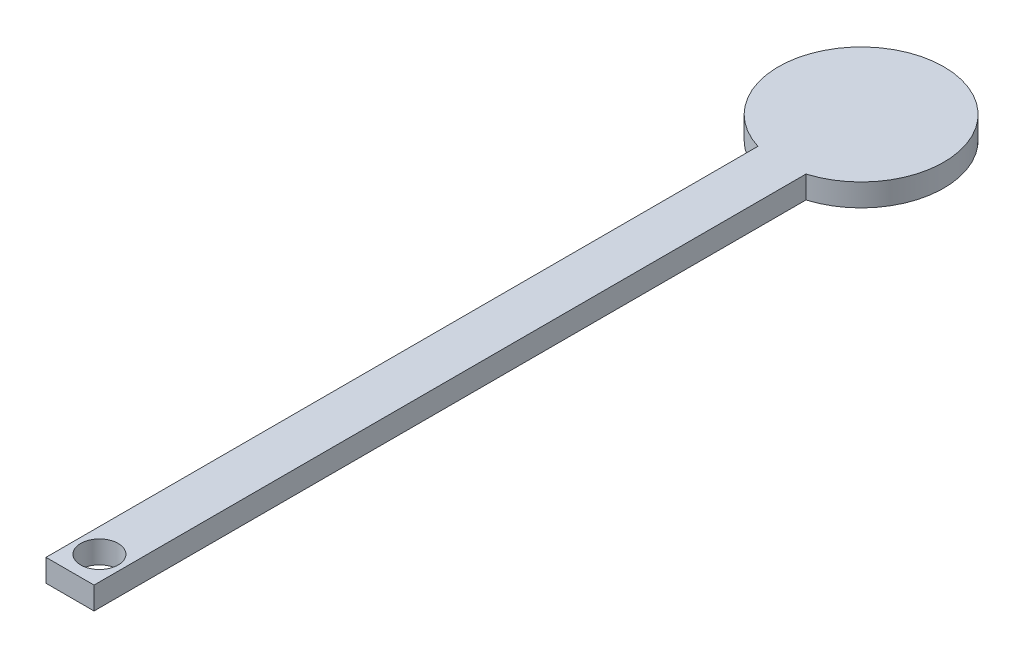
SolidWorks part; units mm, degrees
ref_plane "Front Plane" through (0, 0, 0) normal (0, 0, 1) x (1, 0, 0)
ref_plane "Top Plane" through (0, 0, 0) normal (0, 1, 0) x (1, 0, 0)
ref_plane "Right Plane" through (0, 0, 0) normal (1, 0, 0) x (0, 0, -1)
sketch "Sketch2" plane through (0, 0, 0) normal (0, 1, 0) x (1, 0, 0)
  line L0 (13.2744, 35.7654) -> (13.2744, -125.2511)
  line L5 (-10.6364, -44.7429) -> (24.3636, -44.7429) construction
  line L9 (0.4528, 35.7654) -> (0.4528, -125.2511)
  line L10 (6.8636, 56.8921) -> (6.8636, -44.7429) construction
  line L11 (0.4528, -125.2511) -> (0.4528, -154.2299)
  line L12 (0.4528, -154.2299) -> (13.2744, -154.2299)
  line L13 (13.2744, -154.2299) -> (13.2744, -125.2511)
  circle A1 centre (6.8636, 56.8921) radius 5
  arc A2 (13.2744, 35.7654) -> (0.4528, 35.7654) centre (6.8636, 56.8921) ccw
  circle A5 centre (6.8636, -146.3779) radius 5
  point P4 (0.4528, -44.7429)
  point P5 (13.2744, -44.7429)
  dimension "D3" = 22.078
  dimension "D2" = 10
  dimension "D1" = 101.635
extrude "Boss-Extrude1" add sketch "Sketch2" along normal blind 6
sketch "Sketch3" plane through (0, 6, 0) normal (0, 1, 0) x (1, 0, 0)
  circle A0 centre (6.8636, 56.8921) radius 5
extrude "Boss-Extrude2" add sketch "Sketch3" against normal blind 14
